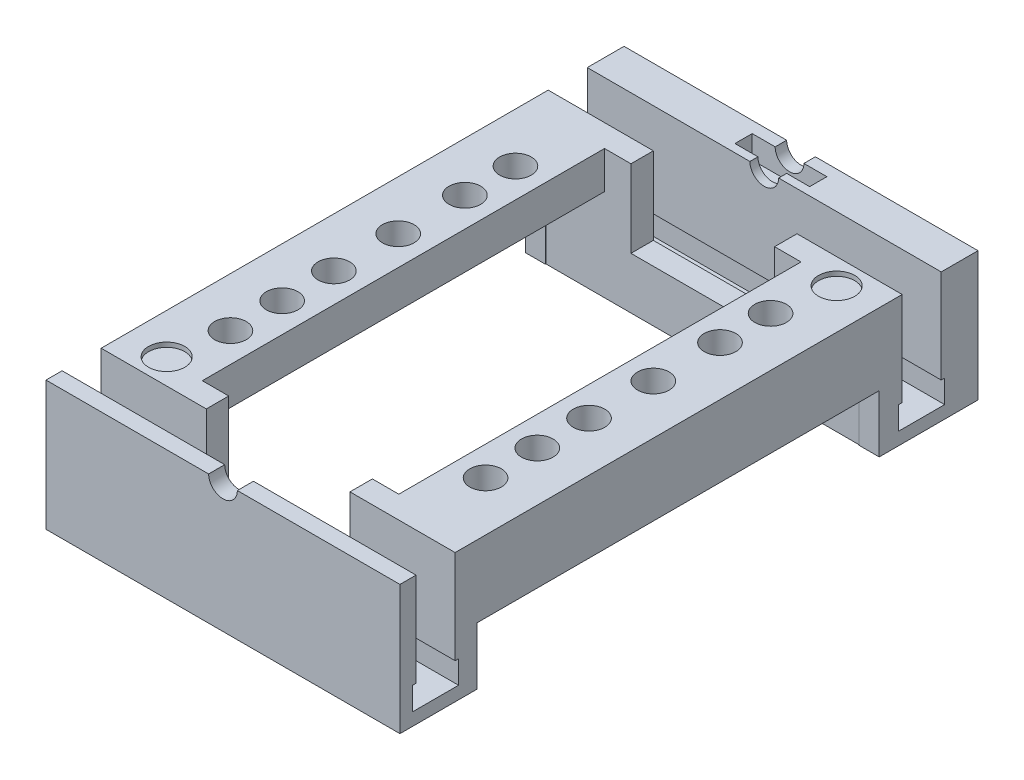
SolidWorks part; units mm, degrees
ref_plane "Front Plane" through (0, 0, 0) normal (0, 0, 1) x (1, 0, 0)
ref_plane "Top Plane" through (0, 0, 0) normal (0, 1, 0) x (1, 0, 0)
ref_plane "Right Plane" through (0, 0, 0) normal (1, 0, 0) x (0, 0, -1)
sketch "Sketch1" plane through (0, 0, 0) normal (0, 0, 1) x (1, 0, 0)
  line L1 (0, 0) -> (78.232, 0)
  line L2 (0, 0) -> (0, 62.23)
  line L3 (0, 62.23) -> (78.232, 62.23)
  line L4 (78.232, 0) -> (78.232, 62.23)
  dimension "D1" = 78.232
  dimension "D2" = 62.23
extrude "Boss-Extrude1" add sketch "Sketch1" along normal blind 128.27
sketch "Sketch2" plane through (0, 0, 0) normal (0, -1, 0) x (1, 0, 0)
  line L0 (0, 128.27) -> (0, 0) construction
  line L1 (17.399, 108.585) -> (60.833, 108.585)
  line L2 (17.399, 108.585) -> (17.399, 19.685)
  line L3 (17.399, 19.685) -> (60.833, 19.685)
  line L4 (60.833, 108.585) -> (60.833, 19.685)
  line L5 (78.232, 128.27) -> (78.232, 0) construction
  line L6 (0, 128.27) -> (78.232, 128.27) construction
  line L7 (0, 0) -> (78.232, 0) construction
  dimension "D1" = 17.399
  dimension "D2" = 17.399
  dimension "D3" = 19.685
  dimension "D4" = 19.685
extrude "Cut-Extrude1" cut sketch "Sketch2" against normal blind 44.45
sketch "Sketch3" plane through (0, 0, 0) normal (0, -1, 0) x (1, 0, 0)
  line L0 (0, 128.27) -> (0, 0) construction
  line L1 (4.445, 108.585) -> (73.787, 108.585)
  line L2 (4.445, 108.585) -> (4.445, 19.685)
  line L3 (4.445, 19.685) -> (73.787, 19.685)
  line L4 (73.787, 108.585) -> (73.787, 19.685)
  line L5 (78.232, 128.27) -> (78.232, 0) construction
  line L6 (17.399, 19.685) -> (60.833, 19.685) construction
  line L7 (60.833, 108.585) -> (17.399, 108.585) construction
  dimension "D1" = 4.445
  dimension "D2" = 4.445
extrude "Cut-Extrude2" cut sketch "Sketch3" against normal blind 22.86
sketch "Sketch4" plane through (0, 0, 0) normal (0, 0, -1) x (-1, 0, 0)
  line L0 (-78.232, 62.23) -> (0, 62.23) construction
  line L1 (0, 62.23) -> (0, 0) construction
  circle A0 centre (-39.116, 31.115) radius 3.175
  point P5 (-39.116, 62.23)
  point P6 (0, 31.115)
  dimension "D1" = 6.35
extrude "Cut-Extrude3" cut sketch "Sketch4" against normal through all both and the other way through all
sketch "Sketch6" plane through (0, 22.86, 0) normal (0, -1, 0) x (1, 0, 0)
  line L0 (60.833, 108.585) -> (60.833, 19.685) construction
  line L4 (17.399, 19.685) -> (17.399, 108.585) construction
  line L8 (4.445, 19.685) -> (17.399, 19.685) construction
  line L9 (60.833, 19.685) -> (73.787, 19.685) construction
  circle A0 centre (10.922, 32.893) radius 3.4925
  circle A1 centre (10.922, 44.069) radius 3.4925
  circle A2 centre (10.922, 58.801) radius 3.4925
  circle A3 centre (10.922, 73.025) radius 3.4925
  circle A4 centre (10.922, 84.455) radius 3.4925
  circle A5 centre (10.922, 95.885) radius 3.4925
  circle A6 centre (67.31, 95.885) radius 3.4925
  circle A8 centre (67.31, 84.455) radius 3.4925
  circle A9 centre (67.31, 73.025) radius 3.4925
  circle A10 centre (67.31, 58.801) radius 3.4925
  circle A11 centre (67.31, 44.069) radius 3.4925
  circle A12 centre (67.31, 32.893) radius 3.4925
  dimension "D1" = 6.985
  dimension "D2" = 6.985
  dimension "D3" = 6.985
  dimension "D4" = 6.985
  dimension "D5" = 6.985
  dimension "D6" = 6.985
  dimension "D7" = 6.985
  dimension "D8" = 11.43
  dimension "D9" = 6.985
  dimension "D10" = 6.985
  dimension "D11" = 6.985
  dimension "D12" = 6.985
  dimension "D13" = 6.985
  dimension "D14" = 6.477
  dimension "D15" = 6.477
  dimension "D16" = 11.176
  dimension "D17" = 11.176
  dimension "D18" = 14.732
  dimension "D19" = 14.224
  dimension "D20" = 14.732
  dimension "D21" = 14.224
  dimension "D22" = 11.43
  dimension "D23" = 11.43
  dimension "D24" = 11.43
  dimension "D25" = 13.208
  dimension "D26" = 13.208
extrude "Cut-Extrude4" cut sketch "Sketch6" against normal through all both and the other way through all
sketch "Sketch7" plane through (78.232, 0, 0) normal (1, 0, 0) x (0, 0, -1)
  line L0 (-122.936, 58.42) -> (-122.936, 53.34)
  line L1 (-122.936, 53.34) -> (-121.412, 53.34)
  line L2 (-121.412, 53.34) -> (-121.412, 10.414)
  line L3 (-121.412, 10.414) -> (-122.936, 10.414)
  line L4 (-122.936, 10.414) -> (-122.936, 5.334)
  line L5 (-122.936, 5.334) -> (-112.776, 5.334)
  line L6 (-112.776, 5.334) -> (-112.776, 10.414)
  line L7 (-112.776, 10.414) -> (-114.3, 10.414)
  line L8 (-114.3, 10.414) -> (-114.3, 53.34)
  line L9 (-114.3, 53.34) -> (-112.776, 53.34)
  line L10 (-112.776, 53.34) -> (-112.776, 58.42)
  line L11 (-112.776, 58.42) -> (-122.936, 58.42)
  line L24 (-128.27, 62.23) -> (0, 62.23) construction
  line L25 (-15.494, 58.42) -> (-15.494, 53.34)
  line L26 (-15.494, 53.34) -> (-13.97, 53.34)
  line L27 (-13.97, 53.34) -> (-13.97, 10.414)
  line L28 (-13.97, 10.414) -> (-15.494, 10.414)
  line L29 (-15.494, 10.414) -> (-15.494, 5.334)
  line L30 (-15.494, 5.334) -> (-5.334, 5.334)
  line L31 (-5.334, 5.334) -> (-5.334, 10.414)
  line L32 (-5.334, 10.414) -> (-6.858, 10.414)
  line L33 (-6.858, 10.414) -> (-6.858, 53.34)
  line L34 (-6.858, 53.34) -> (-5.334, 53.34)
  line L35 (-5.334, 53.34) -> (-5.334, 58.42)
  line L36 (-5.334, 58.42) -> (-15.494, 58.42)
  line L37 (-128.27, 0) -> (-128.27, 62.23) construction
  point P14 (-117.856, 58.42)
  dimension "D1" = 5.08
  dimension "D2" = 1.524
  dimension "D3" = 1.524
  dimension "D4" = 10.16
  dimension "D5" = 10.16
  dimension "D6" = 1.524
  dimension "D7" = 42.926
  dimension "D8" = 3.81
  dimension "D9" = 5.08
  dimension "D10" = 1.524
  dimension "D11" = 1.524
  dimension "D12" = 10.16
  dimension "D13" = 10.16
  dimension "D14" = 1.524
  dimension "D15" = 42.926
  dimension "D16" = 97.282
  dimension "D17" = 5.334
  dimension "D18" = 5.08
  dimension "D19" = 5.08
  dimension "D20" = 3.81
sketch "Sketch8" plane through (78.232, 0, 0) normal (1, 0, 0) x (0, 0, -1)
  line L14 (-128.27, 62.23) -> (-125.73, 62.23)
  line L15 (-128.27, 62.23) -> (-128.27, 0)
  line L17 (-125.73, 62.23) -> (-125.73, 2.54)
  line L19 (-125.73, 2.54) -> (-2.54, 2.54)
  line L21 (-128.27, 0) -> (0, 0)
  line L23 (0, 62.23) -> (-2.54, 62.23)
  line L24 (0, 62.23) -> (0, 0)
  line L26 (-2.54, 62.23) -> (-2.54, 2.54)
  dimension "D1" = 2.54
  dimension "D2" = 2.54
  dimension "D3" = 2.54
extrude "Cut-Extrude6" cut sketch "Sketch7" against normal through all both and the other way through all
extrude "Cut-Extrude7" cut sketch "Sketch8" against normal through all both and the other way through all
sketch "Sketch9" plane through (0, 0, 2.54) normal (0, 0, -1) x (-1, 0, 0)
  line L0 (0, 62.23) -> (-78.232, 62.23) construction
  line L1 (-61.341, 59.69) -> (-16.891, 59.69)
  line L2 (-61.341, 59.69) -> (-61.341, 54.61)
  line L3 (-61.341, 54.61) -> (-16.891, 54.61)
  line L4 (-16.891, 59.69) -> (-16.891, 54.61)
  point P6 (-39.116, 62.23)
  point P7 (-39.116, 59.69)
  dimension "D1" = 44.45
  dimension "D2" = 5.08
  dimension "D3" = 2.54
extrude "Cut-Extrude8" cut sketch "Sketch9" against normal blind 107.95 and the other way through all
sketch "Sketch10" plane through (0, 62.23, 0) normal (0, 1, 0) x (1, 0, 0)
  line L0 (0, -2.54) -> (78.232, -2.54) construction
  line L1 (20.193, -24.13) -> (58.293, -24.13)
  line L2 (20.193, -24.13) -> (20.193, -104.14)
  line L3 (20.193, -104.14) -> (58.293, -104.14)
  line L4 (58.293, -24.13) -> (58.293, -104.14)
  line L6 (78.232, -125.73) -> (78.232, -2.54) construction
  dimension "D1" = 38.1
  dimension "D2" = 80.01
  dimension "D3" = 21.59
  dimension "D4" = 19.939
extrude "Cut-Extrude9" cut sketch "Sketch10" against normal blind 19.05
sketch "Sketch11" plane through (0, 0, 108.585) normal (0, 0, -1) x (-1, 0, 0)
  line L0 (0, 62.23) -> (-78.232, 62.23) construction
  line L1 (-54.991, 48.26) -> (-23.241, 48.26)
  line L2 (-54.991, 48.26) -> (-54.991, 13.97)
  line L3 (-54.991, 13.97) -> (-23.241, 13.97)
  line L4 (-23.241, 48.26) -> (-23.241, 13.97)
  line L6 (0, 62.23) -> (0, 2.54) construction
  dimension "D1" = 31.75
  dimension "D2" = 34.29
  dimension "D3" = 13.97
  dimension "D4" = 23.241
extrude "Cut-Extrude10" cut sketch "Sketch11" along normal blind 101.6 from offset 6.35 offset against normal yes
sketch "Sketch12" plane through (0, 0, 125.73) normal (0, 0, 1) x (1, 0, 0)
  line L0 (78.232, 62.23) -> (78.232, 2.54) construction
  line L1 (0, 62.23) -> (78.232, 62.23)
  line L2 (0, 62.23) -> (0, 31.115)
  line L3 (0, 31.115) -> (78.232, 31.115)
  line L4 (78.232, 62.23) -> (78.232, 31.115)
  dimension "D1" = 31.115
extrude "Cut-Extrude11" cut sketch "Sketch12" against normal through all both and the other way through all
sketch "Sketch13" plane through (0, 31.115, 0) normal (0, 1, 0) x (1, 0, 0)
  line L2 (78.232, -125.73) -> (42.291, -125.73) construction
  line L3 (78.232, -13.97) -> (78.232, -114.3) construction
  line L4 (42.291, -2.54) -> (78.232, -2.54) construction
  line L5 (0, -13.97) -> (0, -114.3) construction
  circle A0 centre (69.342, -20.32) radius 4.0005
  circle A1 centre (8.89, -107.95) radius 4.0005
  dimension "D3" = 8.001
  dimension "D6" = 8.001
  dimension "D1" = 8.89
  dimension "D2" = 17.78
  dimension "D4" = 17.78
  dimension "D5" = 8.89
ref_plane "Plane1" through (35.941, 31.115, 125.73) normal (0, 0, 1) x (1, 0, 0)
sketch "Sketch16" plane through (0, 0, 125.73) normal (0, 0, 1) x (1, 0, 0)
  line L0 (0, 31.115) -> (35.941, 31.115)
  line L1 (42.291, 31.115) -> (78.232, 31.115)
  line L2 (78.232, 31.115) -> (78.232, 2.54)
  line L3 (78.232, 2.54) -> (0, 2.54)
  line L4 (0, 2.54) -> (0, 31.115)
  arc A0 (35.941, 31.115) -> (39.116, 27.94) centre (39.116, 31.115) ccw
  arc A1 (35.941, 31.115) -> (42.291, 31.115) centre (39.116, 31.115) ccw construction
  arc A2 (39.116, 27.94) -> (42.291, 31.115) centre (39.116, 31.115) ccw
sketch "Sketch17" plane through (0, 0, 2.54) normal (0, 0, -1) x (-1, 0, 0)
  line L0 (-78.232, 31.115) -> (-42.291, 31.115)
  line L1 (-35.941, 31.115) -> (0, 31.115)
  line L2 (0, 31.115) -> (0, 2.54)
  line L3 (0, 2.54) -> (-78.232, 2.54)
  line L4 (-78.232, 2.54) -> (-78.232, 31.115)
  arc A0 (-42.291, 31.115) -> (-39.116, 27.94) centre (-39.116, 31.115) ccw
  arc A1 (-39.116, 27.94) -> (-35.941, 31.115) centre (-39.116, 31.115) ccw
extrude "Boss-Extrude4" add sketch "Sketch17" along normal blind 4.572
sketch "Sketch18" plane through (0, 31.115, 0) normal (0, 1, 0) x (1, 0, 0)
  line L0 (42.291, 2.032) -> (78.232, 2.032) construction
  line L1 (30.861, -0.508) -> (47.371, -0.508)
  line L2 (30.861, -0.508) -> (30.861, -4.318)
  line L3 (30.861, -4.318) -> (47.371, -4.318)
  line L4 (47.371, -0.508) -> (47.371, -4.318)
  line L5 (78.232, 2.032) -> (78.232, -6.858) construction
  dimension "D1" = 16.51
  dimension "D2" = 3.81
  dimension "D3" = 2.54
  dimension "D4" = 30.861
extrude "Cut-Extrude12" cut sketch "Sketch18" against normal blind 5.08 and the other way through all
sketch "Sketch19" plane through (73.787, 0, 0) normal (-1, 0, 0) x (0, 0, 1)
  line L0 (-2.032, 2.54) -> (125.73, 2.54) construction
  line L1 (19.7986, 15.24) -> (108.6986, 15.24)
  line L2 (19.7986, 15.24) -> (19.7986, 2.54)
  line L3 (19.7986, 2.54) -> (108.6986, 2.54)
  line L4 (108.6986, 15.24) -> (108.6986, 2.54)
  dimension "D1" = 12.7
  dimension "D2" = 88.9
extrude "Cut-Extrude13" cut sketch "Sketch19" against normal through all both and the other way through all
extrude "Cut-Extrude14" cut sketch "Sketch13" against normal blind 1.016
other "Move Face1" face at (39.116, 23.6855, 6.858) face at (39.116, 21.6535, 13.97) face at (39.116, 21.6535, 114.3) face at (39.116, 23.6855, 121.412) parameters "D1"=0.762
